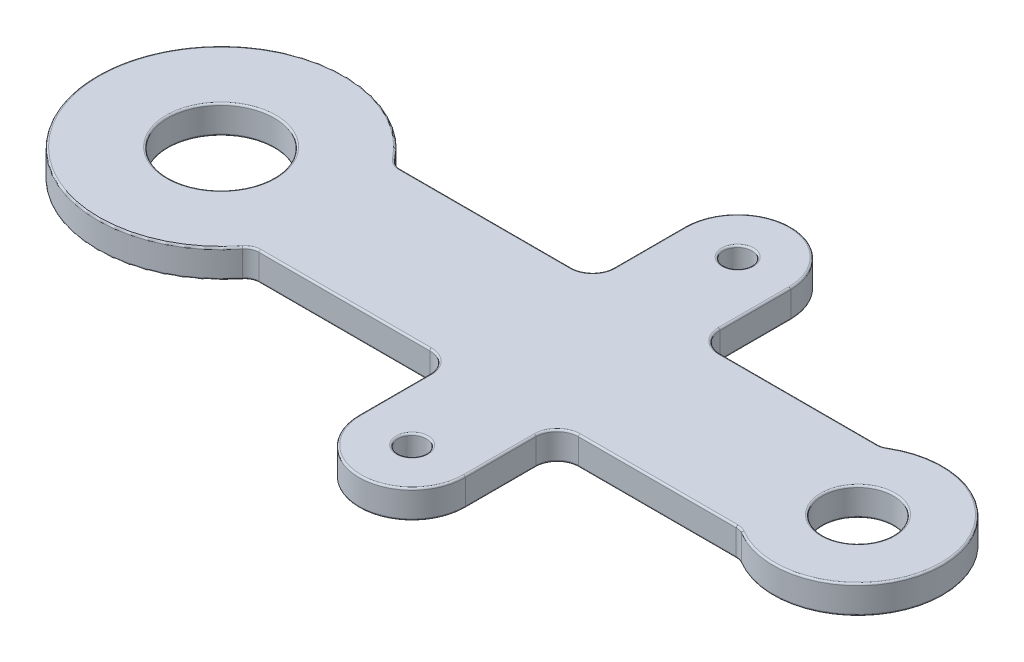
SolidWorks part; units mm, degrees
ref_plane "前视基准面" through (0, 0, 0) normal (0, 0, 1) x (1, 0, 0)
ref_plane "上视基准面" through (0, 0, 0) normal (0, 1, 0) x (1, 0, 0)
ref_plane "右视基准面" through (0, 0, 0) normal (1, 0, 0) x (0, 0, -1)
sketch "草图1" plane through (0, 0, 0) normal (0, 1, 0) x (1, 0, 0)
  line L0 (-79.8254, 0) -> (43.5663, 0) construction
  line L1 (0, 81.5805) -> (0, -29.6577) construction
  line L2 (28.7194, 20.0049) -> (85, 20.0049)
  line L3 (28.7194, -20.0049) -> (85, -20.0049)
  line L4 (115, 20.0049) -> (166.7409, 20.0049)
  line L5 (115, -20.0049) -> (166.7409, -20.0049)
  line L7 (85, 46) -> (85, 20.0049)
  line L8 (115, 46) -> (115, 20.0049)
  line L9 (115, -46) -> (115, -20.0049)
  line L10 (85, -46) -> (85, -20.0049)
  circle A0 centre (0, 0) radius 15
  arc A1 (28.7194, 20.0049) -> (28.7194, -20.0049) centre (0, 0) ccw
  circle A2 centre (100, 46) radius 4
  circle A3 centre (180, 0) radius 10
  arc A4 (166.7409, -20.0049) -> (166.7409, 20.0049) centre (180, 0) ccw
  circle A5 centre (100, -46) radius 4
  arc A8 (115, 46) -> (85, 46) centre (100, 46) ccw
  arc A9 (115, -46) -> (85, -46) centre (100, -46) cw
  point P9 (180, 0)
  point P13 (28.7194, 20.0049)
  point P24 (100, 0)
  point P29 (85, 46)
  point P30 (115, 46)
extrude "凸台-拉伸1" add sketch "草图1" along normal blind 8
fillet "圆角3" radius 6 1 edges at (115, 4, 20.0049)
fillet "圆角4" radius 6 1 edges at (85, 4, 20.0049)
fillet "圆角5" radius 6 1 edges at (85, 4, -20.0049)
fillet "圆角6" radius 6 1 edges at (115, 4, -20.0049)
fillet "圆角8" radius 4 1 edges at (166.7409, 4, -20.0049)
fillet "圆角9" radius 4 1 edges at (166.7409, 4, 20.0049)
fillet "圆角10" radius 4 1 edges at (28.7194, 4, 20.0049)
fillet "圆角11" radius 4 1 edges at (28.7194, 4, -20.0049)
fillet "圆角12" radius 0.5 48 edges at (100, 0, 42) (180, 0, 10) (100, 0, -42) (0, 0, 15) (28.9832, 0, 20.4099) (54.8685, 0, 20.0049) (83.2426, 0, 21.7622) (85, 0, 36.0024) (100, 0, 61) (115, 0, 36.0024) (116.7574, 0, 21.7622) (143.293, 0, 20.0049) (166.6543, 0, 20.1502) (204, 0, 0) (166.6543, 0, -20.1502) (143.293, 0, -20.0049) (116.7574, 0, -21.7622) (115, 0, -36.0024) (100, 0, -61) (85, 0, -36.0024) (83.2426, 0, -21.7622) (54.8685, 0, -20.0049) (28.9832, 0, -20.4099) (-35, 0, 0) (100, 8, 42) (100, 8, -42) (0, 8, 15) (180, 8, 10) (54.8685, 8, -20.0049) (83.2426, 8, -21.7622) (85, 8, -36.0024) (100, 8, -61) (115, 8, -36.0024) (116.7574, 8, -21.7622) (143.293, 8, -20.0049) (166.6543, 8, -20.1502) (204, 8, 0) (166.6543, 8, 20.1502) (143.293, 8, 20.0049) (116.7574, 8, 21.7622) (115, 8, 36.0024) (100, 8, 61) (85, 8, 36.0024) (83.2426, 8, 21.7622) (54.8685, 8, 20.0049) (28.9832, 8, 20.4099) (-35, 8, 0) (28.9832, 8, -20.4099)
